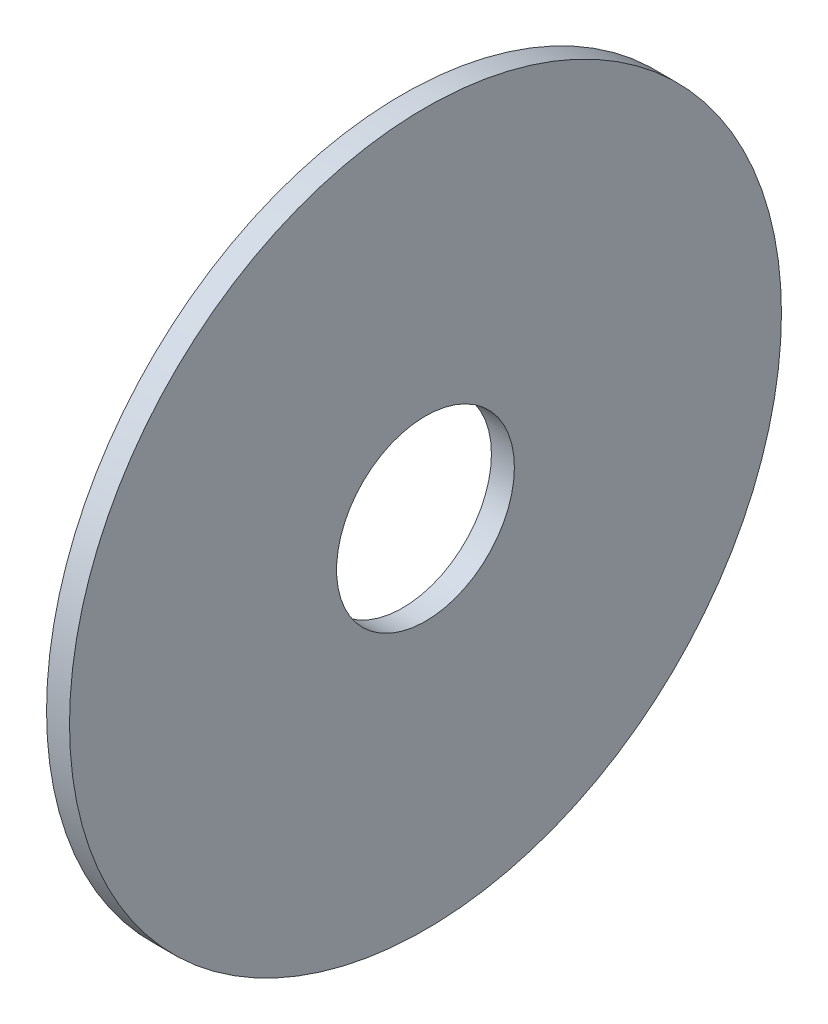
SolidWorks part; units mm, degrees
ref_plane "Alzado" through (0, 0, 0) normal (0, 0, 1) x (1, 0, 0)
ref_plane "Planta" through (0, 0, 0) normal (0, 1, 0) x (1, 0, 0)
ref_plane "Vista lateral" through (0, 0, 0) normal (1, 0, 0) x (0, 0, -1)
sketch "Croquis1" plane through (0, 0, 0) normal (1, 0, 0) x (0, 0, -1)
  circle A0 centre (0, 0) radius 70.07
  circle A1 centre (0, 0) radius 17.5
  dimension "D1" = 140.14
  dimension "D2" = 35
extrude "Saliente-Extruir1" add sketch "Croquis1" along normal blind 4.52
